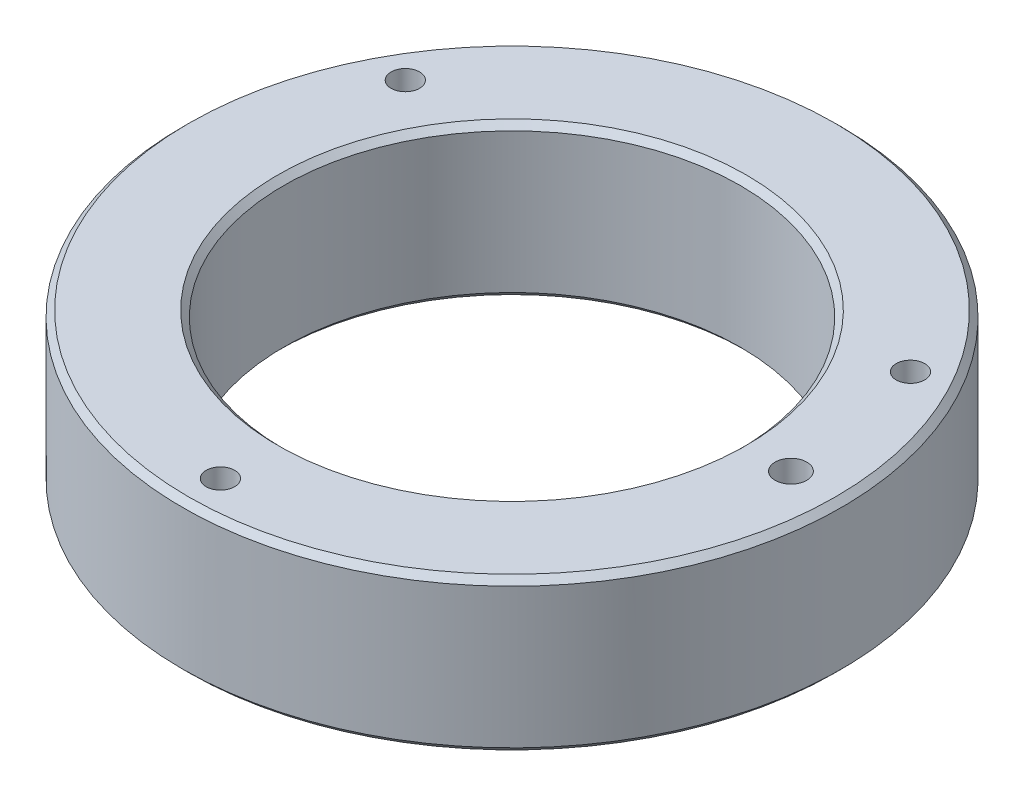
SolidWorks part; units mm, degrees
ref_plane "Front Plane" through (0, 0, 0) normal (1, 0, 0) x (0, 1, 0)
ref_plane "Top Plane" through (0, 0, 0) normal (0, 0, 1) x (0, 1, 0)
ref_plane "Right Plane" through (0, 0, 0) normal (0, 1, 0) x (-1, 0, 0)
sketch "Sketch1" plane through (0, 0, 0) normal (0, 0, 1) x (0, 1, 0)
  line L0 (-19.05, 82.5246) -> (19.05, 82.5246)
  line L1 (19.05, 82.5246) -> (19.05, 57.15)
  line L2 (19.05, 57.15) -> (-19.05, 57.15)
  line L3 (-19.05, 57.15) -> (-19.05, 82.5246)
  line L4 (-44.45, 0) -> (44.45, 0) construction
revolve "Revolve1" add sketch "Sketch1" angle 360 about L4
hole_wizard "CBORE for 1/4 Socket Head Cap Screw1" positions "Sketch3" profile "Sketch2" counterbore size "1/4" standard "ANSI Inch"
sketch "Sketch3" plane through (0, -19.05, 0) normal (0, -1, 0) x (-1, 0, 0)
  point P0 (0, -73.025)
  point P1 (-63.246, 36.5252)
  point P3 (63.246, 36.5252)
sketch "Sketch2" plane through (0, -19.05, 73.025) normal (1, 0, 0) x (0, 0, -1)
  line L0 (0, 0) -> (0, 40.2443)
  line L1 (0, 40.2443) -> (3.5687, 38.1)
  line L2 (3.5687, 38.1) -> (3.5687, 9.652)
  line L3 (3.5687, 9.652) -> (5.5626, 9.652)
  line L4 (5.5626, 9.652) -> (5.5626, 0)
  line L5 (5.5626, 0) -> (0, 0)
  line L10 (0, 40.2443) -> (-3.5687, 38.1) construction
  line L11 (0, -6.35) -> (0, 107.95) construction
  dimension "Hole Dia." = 7.1374
  dimension "Hole Depth" = 38.1
  dimension "C'Bore Dia." = 11.1252
  dimension "C'Bore Depth" = 9.652
  dimension "Drill Angle" = 118
hole_wizard "3/8-16 Tapped Hole1" positions "Sketch5" profile "Sketch4" tap size "3/8-16" standard "ANSI Inch"
sketch "Sketch5" plane through (0, -19.05, 0) normal (0, -1, 0) x (-1, 0, 0)
  point P0 (-69.85, 0)
sketch "Sketch4" plane through (69.85, -19.05, 0) normal (1, 0, 0) x (0, 0, -1)
  line L0 (0, 0) -> (0, 40.4847)
  line L1 (0, 40.4847) -> (3.9687, 38.1)
  line L2 (3.9687, 38.1) -> (3.9687, 0)
  line L5 (3.9687, 0) -> (0, 0)
  line L10 (0, 40.4847) -> (-3.9688, 38.1) construction
  line L11 (0, -6.35) -> (0, 107.95) construction
  dimension "Tap Drill Dia." = 7.9375
  dimension "Tap Drill Depth" = 38.1
  dimension "Drill Angle" = 118
cosmetic thread "Hole Thread1" parameters "D1"=19.05, "D2"=9.525
chamfer "Chamfer1" distance 1.524 angle 45 4 edges at (0, 19.05, -57.15) (0, -19.05, -57.15) (0, 19.05, -82.5246) (0, -19.05, -82.5246)
